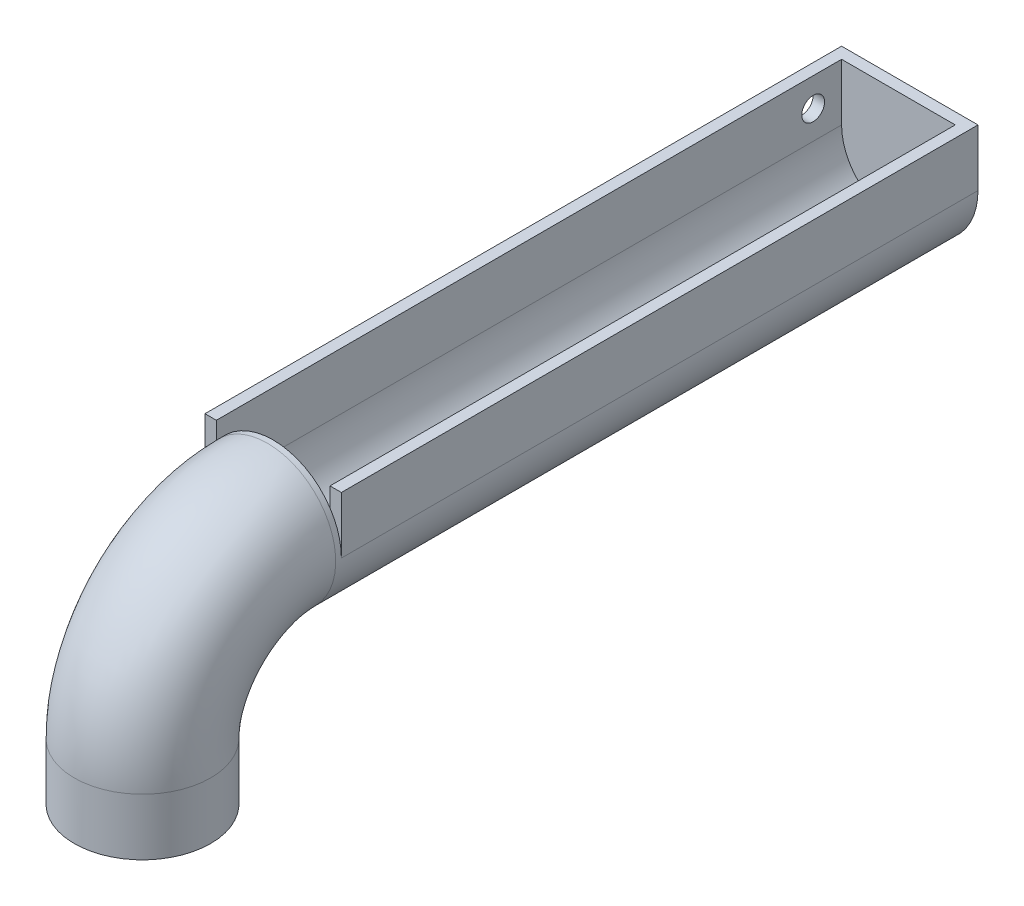
SolidWorks part; units mm, degrees
ref_plane "Front Plane" through (0, 0, 0) normal (0, 0, 1) x (1, 0, 0)
ref_plane "Top Plane" through (0, 0, 0) normal (0, 1, 0) x (1, 0, 0)
ref_plane "Right Plane" through (0, 0, 0) normal (1, 0, 0) x (0, 0, -1)
sketch "Sketch1" plane through (0, 0, 0) normal (0, 0, 1) x (1, 0, 0)
  line L0 (-10, 0) -> (-10, 10)
  line L2 (10, 10) -> (10, 0)
  line L3 (12, 10) -> (12, 0)
  line L4 (-12, 0) -> (-12, 10)
  line L5 (-12, 10) -> (-10, 10)
  line L6 (10, 10) -> (12, 10)
  arc A2 (-10, 0) -> (10, 0) centre (0, 0) ccw
  arc A3 (-12, 0) -> (12, 0) centre (0, 0) ccw
  dimension "D1" = 10
  dimension "D2" = 10
  dimension "D3" = 2
extrude "Boss-Extrude1" add sketch "Sketch1" along normal blind 110
sketch "Sketch8" plane through (0, 0, 110) normal (0, 0, 1) x (1, 0, 0)
  line L0 (-12, 10) -> (12, 10)
  line L1 (-12, 10) -> (-12, 0)
  line L2 (12, 10) -> (12, 0)
  arc A0 (-12, 0) -> (12, 0) centre (0, 0) ccw
extrude "Boss-Extrude3" add sketch "Sketch8" against normal blind 2 from surface at -110 starting at face at (0, 2.25, 0)
ref_plane "Plane3" through (0, 0, 110) normal (0, 0, 1) x (1, 0, 0)
sketch "Sketch12" plane through (0, 0, 110) normal (0, 0, 1) x (1, 0, 0)
  line L0 (-12, 10) -> (-10, 10)
  line L1 (-10, 10) -> (-10, 0)
  line L2 (10, 0) -> (10, 10)
  line L3 (10, 10) -> (12, 10)
  line L4 (12, 10) -> (12, 0)
  line L5 (-12, 0) -> (-12, 10)
  arc A0 (-10, 0) -> (10, 0) centre (0, 0) ccw
  arc A1 (12, 0) -> (-12, 0) centre (0, 0) cw
sketch "Sketch15" plane through (-12, 0, 0) normal (-1, 0, 0) x (0, 0, 1)
  line L1 (110, 10) -> (-2, 10) construction
  line L3 (-2, 10) -> (-2, 0) construction
  circle A0 centre (5, 5) radius 2.005
  dimension "D1" = 4.01
  dimension "D3" = 5
  dimension "D2" = 7
extrude "Cut-Extrude1" cut sketch "Sketch15" against normal blind 2
ref_plane "Plane4" through (0, 0, 0) normal (1, 0, 0) x (0, 0, -1)
sketch "Sketch17" plane through (0, 0, 0) normal (1, 0, 0) x (0, 0, -1)
  line L0 (-110, -12) -> (-111, -12)
  line L1 (-121, -22) -> (-121, -32)
  arc A0 (-111, -12) -> (-121, -22) centre (-111, -22) ccw
  dimension "D2" = 10
  dimension "D1" = 1
  dimension "D3" = 10
sketch "Sketch18" plane through (0, 0, 110) normal (0, 0, 1) x (1, 0, 0)
  circle A0 centre (0, 0) radius 10
  circle A1 centre (0, 0) radius 12
  dimension "D1" = 24
  dimension "D2" = 20
sweep "Sweep2" add profiles "Sketch18" path "Sketch17"
